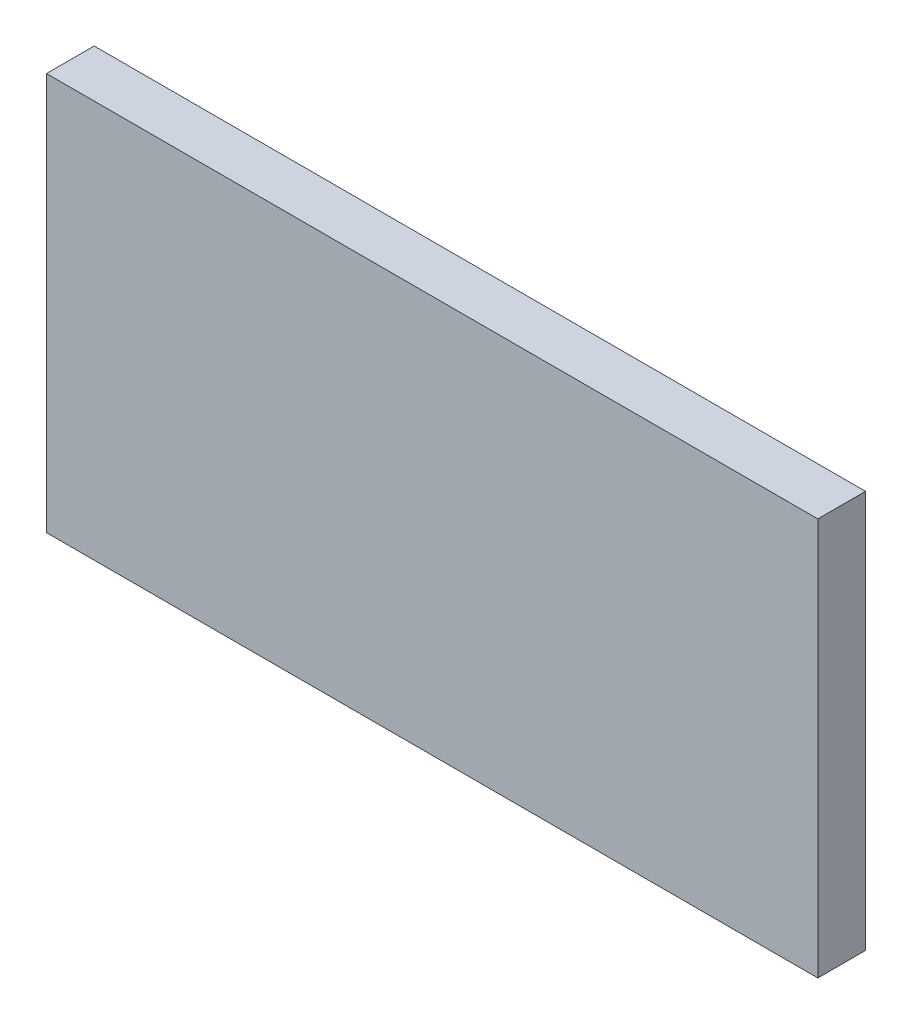
SolidWorks part; units mm, degrees
ref_plane "Спереди" through (0, 0, 0) normal (0, 0, 1) x (1, 0, 0)
ref_plane "Сверху" through (0, 0, 0) normal (0, 1, 0) x (1, 0, 0)
ref_plane "Справа" through (0, 0, 0) normal (1, 0, 0) x (0, 0, -1)
other "Configuration Table"
sketch "Эскиз1" plane through (0, 0, 0) normal (0, 0, 1) x (1, 0, 0)
  line L1 (48.5, 25) -> (-48.5, 25)
  line L2 (48.5, 25) -> (48.5, -25)
  line L3 (48.5, -25) -> (-48.5, -25)
  line L4 (-48.5, 25) -> (-48.5, -25)
  line L5 (48.5, 25) -> (-48.5, -25) construction
  line L6 (48.5, -25) -> (-48.5, 25) construction
  point P0 (0, 0)
  dimension "D1" = 50
  dimension "D2" = 97
extrude "Бобышка-Вытянуть1" add sketch "Эскиз1" along normal blind 6
